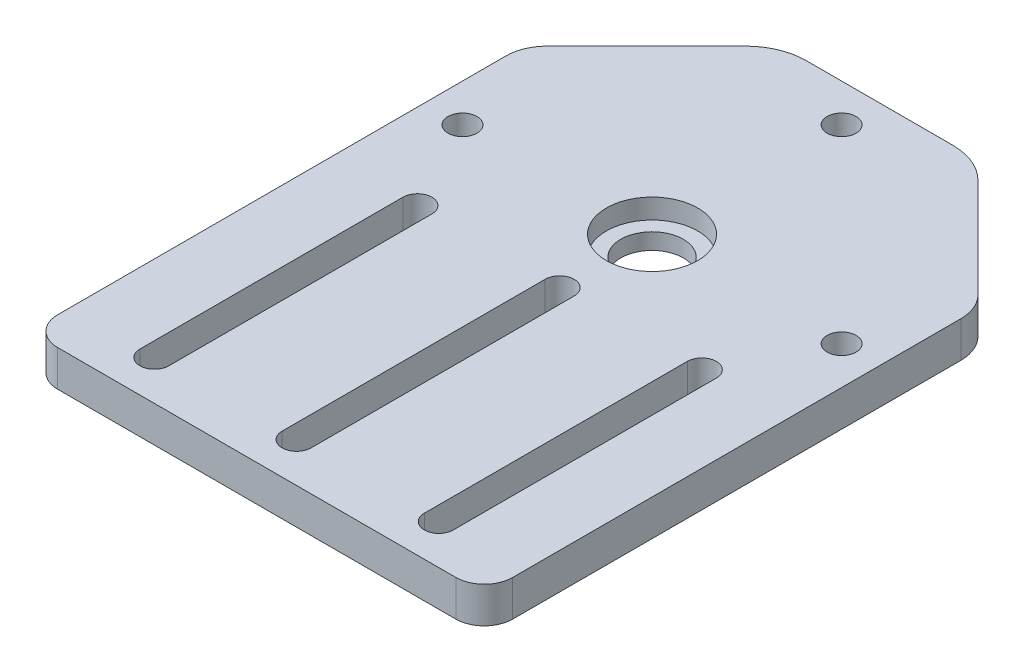
SolidWorks part; units mm, degrees
material "6063-T6"
ref_plane "Front Plane" through (0, 0, 0) normal (0, 0, 1) x (1, 0, 0)
ref_plane "Top Plane" through (0, 0, 0) normal (0, 1, 0) x (1, 0, 0)
ref_plane "Right Plane" through (0, 0, 0) normal (1, 0, 0) x (0, 0, -1)
sketch "Sketch1" plane through (0, 0, 0) normal (0, 1, 0) x (1, 0, 0)
  line L0 (0, 0) -> (21.9203, 0) construction
  line L1 (35, -32.5) -> (-35, -32.5) construction
  line L2 (40, -27.5) -> (40, 14.307)
  line L3 (12.8862, 40) -> (-12.8862, 40)
  line L4 (-40, -27.5) -> (-40, 14.307)
  line L5 (0, 21.9203) -> (0, 0) construction
  line L6 (-37.8765, 19.4335) -> (-20.4381, 36.8719)
  line L7 (37.8765, 19.4335) -> (20.4381, 36.8719)
  line L14 (25, -62.5) -> (25, -16.25) construction
  line L15 (22.45, -62.5) -> (22.45, -16.25)
  line L16 (27.55, -62.5) -> (27.55, -16.25)
  line L17 (0, -62.5) -> (0, -16.25) construction
  line L18 (-2.55, -62.5) -> (-2.55, -16.25)
  line L19 (2.55, -62.5) -> (2.55, -16.25)
  line L20 (-25, -62.5) -> (-25, -16.25) construction
  line L21 (-27.55, -62.5) -> (-27.55, -16.25)
  line L22 (-22.45, -62.5) -> (-22.45, -16.25)
  line L30 (0, 0) -> (-33.333, 0) construction
  line L31 (0, 0) -> (0, 33.333) construction
  line L32 (-40, -27.5) -> (-40, -64.5)
  line L33 (-35, -69.5) -> (35, -69.5)
  line L34 (40, -64.5) -> (40, -27.5)
  arc A0 (-35, -32.5) -> (-40, -27.5) centre (-35, -27.5) cw construction
  arc A1 (35, -32.5) -> (40, -27.5) centre (35, -27.5) ccw construction
  circle A2 centre (21.9203, 0) radius 1.6 construction
  circle A3 centre (-21.9203, 0) radius 1.6 construction
  circle A4 centre (0, 0) radius 5.5
  circle A5 centre (0, 21.9203) radius 1.6 construction
  arc A10 (22.45, -62.5) -> (27.55, -62.5) centre (25, -62.5) ccw
  arc A11 (27.55, -16.25) -> (22.45, -16.25) centre (25, -16.25) ccw
  arc A12 (-2.55, -62.5) -> (2.55, -62.5) centre (0, -62.5) ccw
  arc A13 (2.55, -16.25) -> (-2.55, -16.25) centre (0, -16.25) ccw
  arc A14 (-27.55, -62.5) -> (-22.45, -62.5) centre (-25, -62.5) ccw
  arc A15 (-22.45, -16.25) -> (-27.55, -16.25) centre (-25, -16.25) ccw
  arc A16 (-37.8765, 19.4335) -> (-40, 14.307) centre (-32.75, 14.307) ccw
  arc A17 (37.8765, 19.4335) -> (40, 14.307) centre (32.75, 14.307) cw
  arc A18 (-20.4381, 36.8719) -> (-12.8862, 40) centre (-12.8862, 29.32) cw
  arc A19 (12.8862, 40) -> (20.4381, 36.8719) centre (12.8862, 29.32) cw
  circle A24 centre (-33.333, 0) radius 2.55
  circle A25 centre (0, 33.333) radius 2.55
  circle A26 centre (33.333, 0) radius 2.55
  arc A27 (40, -64.5) -> (35, -69.5) centre (35, -64.5) cw
  arc A28 (-35, -69.5) -> (-40, -64.5) centre (-35, -64.5) cw
  point P36 (25, -39.375)
  point P43 (0, -39.375)
  point P50 (-25, -39.375)
  point P58 (-40, 17.31)
  point P61 (40, 17.31)
  point P64 (-17.31, 40)
  point P67 (17.31, 40)
  dimension "D2" = 5
  dimension "D3" = 32.5
  dimension "D5" = 45
  dimension "D7" = 31
  dimension "D10" = 25
  dimension "D4" = 11
  dimension "D8" = 3.2
  dimension "D15" = 7.25
  dimension "D17" = 5.1
  dimension "D6" = 34.62
  dimension "D16" = 10.68
  dimension "D20" = 5
  dimension "D1" = 72.5
  dimension "D9" = 80
  dimension "D11" = 16.25
  dimension "D12" = 37
  dimension "D13" = 25
  dimension "D18" = 47.14
extrude "Boss-Extrude1" add sketch "Sketch1" along normal blind 6.35
sketch "Sketch2" plane through (0, 6.35, 0) normal (0, 1, 0) x (1, 0, 0)
  circle A0 centre (0, 0) radius 8.025
  dimension "D1" = 16.05
extrude "Cut-Extrude1" cut sketch "Sketch2" against normal blind 3.5
